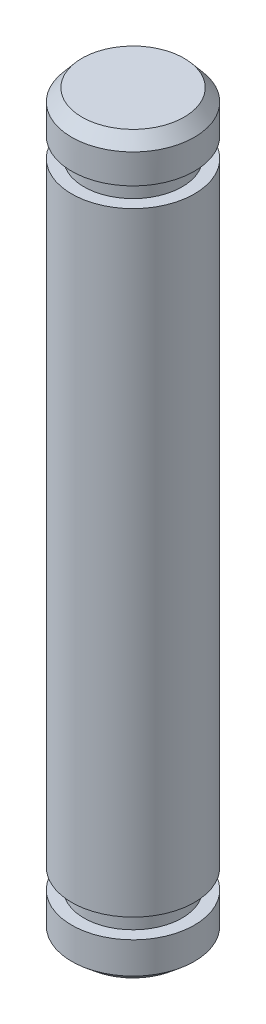
SolidWorks part; units mm, degrees
ref_plane "前视基准面" through (0, 0, 0) normal (0, 0, 1) x (1, 0, 0)
ref_plane "上视基准面" through (0, 0, 0) normal (0, 1, 0) x (1, 0, 0)
ref_plane "右视基准面" through (0, 0, 0) normal (1, 0, 0) x (0, 0, -1)
other "Configuration Table"
sketch "草图1" plane through (0, 0, 0) normal (0, 1, 0) x (1, 0, 0)
  circle A0 centre (0, 0) radius 2.5
  dimension "D1" = 5
extrude "凸台-拉伸1" add sketch "草图1" along normal blind 15
ref_plane "基准面1" through (0, 12.5, 0) normal (0, -1, 0) x (-1, 0, 0)
sketch "草图2" plane through (0, 12.5, 0) normal (0, -1, 0) x (-1, 0, 0)
  circle A0 centre (0, 0) radius 2
  circle A1 centre (0, 0) radius 2.5
  dimension "D1" = 4
  dimension "D2" = 5
extrude "切除-拉伸1" cut sketch "草图2" against normal blind 0.8
mirror "镜向1" about plane through (0, 0, 0) normal (0, 1, 0) of "切除-拉伸1", "凸台-拉伸1"
chamfer "倒角1" distance 0.5 angle 40 2 edges at (0, 15, 2.5) (0, -15, 2.5)
equation "\"0。8\"=15"
